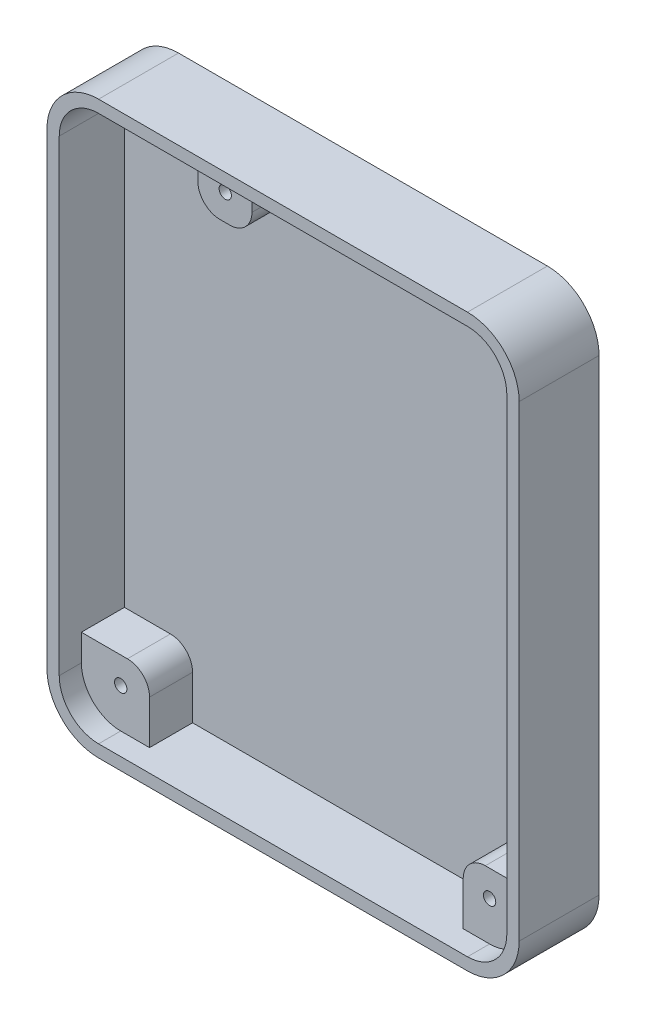
SolidWorks part; units mm, degrees
ref_plane "Спереди" through (0, 0, 0) normal (0, 0, 1) x (1, 0, 0)
ref_plane "Сверху" through (0, 0, 0) normal (0, 1, 0) x (1, 0, 0)
ref_plane "Справа" through (0, 0, 0) normal (1, 0, 0) x (0, 0, -1)
sketch "Эскиз1" plane through (0, 0, 0) normal (0, 0, 1) x (1, 0, 0)
  line L0 (36.05, 3) -> (35.95, 3)
  line L1 (35.95, 3) -> (35.95, 41)
  line L2 (35.95, 41) -> (36.05, 41)
  line L3 (36.05, 41) -> (36.05, 3)
  line L4 (3, 43.95) -> (3, 44.05)
  line L5 (3, 44.05) -> (33, 44.05)
  line L6 (33, 44.05) -> (33, 43.95)
  line L7 (33, 43.95) -> (3, 43.95)
  line L8 (0.05, 3) -> (-0.05, 3)
  line L9 (-0.05, 3) -> (-0.05, 41)
  line L10 (-0.05, 41) -> (0.05, 41)
  line L11 (0.05, 41) -> (0.05, 3)
  line L12 (3, -0.05) -> (3, 0.05)
  line L13 (3, 0.05) -> (33, 0.05)
  line L14 (33, 0.05) -> (33, -0.05)
  line L15 (33, -0.05) -> (3, -0.05)
  circle A0 centre (36, 3) radius 0.05
  circle A1 centre (36, 41) radius 0.05
  circle A2 centre (3, 44) radius 0.05
  circle A3 centre (33, 44) radius 0.05
  circle A4 centre (0, 3) radius 0.05
  circle A5 centre (0, 41) radius 0.05
  circle A6 centre (3, 0) radius 0.05
  circle A7 centre (33, 0) radius 0.05
  arc A8 (36, 41) -> (33, 44) centre (33, 41) ccw
  circle A9 centre (33, 44) radius 0.05
  circle A10 centre (36, 41) radius 0.05
  arc A11 (33, 0) -> (36, 3) centre (33, 3) ccw
  circle A12 centre (36, 3) radius 0.05
  circle A13 centre (33, 0) radius 0.05
  arc A14 (3, 44) -> (0, 41) centre (3, 41) ccw
  circle A15 centre (0, 41) radius 0.05
  circle A16 centre (3, 44) radius 0.05
  arc A17 (0, 3) -> (3, 0) centre (3, 3) ccw
  circle A18 centre (3, 0) radius 0.05
  circle A19 centre (0, 3) radius 0.05
  circle A20 centre (11.5, 42) radius 1
  circle A21 centre (33, 3) radius 1
  circle A22 centre (3, 3) radius 1
sketch "Эскиз2" plane through (0, 0, 0) normal (0, 0, 1) x (1, 0, 0)
  line L0 (3, 44.2) -> (33, 44.2)
  line L1 (36.2, 41) -> (36.2, 3)
  line L2 (-0.2, 41) -> (-0.2, 3)
  line L3 (3, -0.2) -> (33, -0.2)
  line L4 (3, 45.2) -> (33, 45.2)
  line L5 (37.2, 41) -> (37.2, 3)
  line L6 (3, -1.2) -> (33, -1.2)
  line L7 (-1.2, 41) -> (-1.2, 3)
  arc A2 (3, 44.2) -> (-0.2, 41) centre (3, 41) ccw
  arc A3 (3, 44.2) -> (-0.2, 41) centre (3, 41) ccw
  arc A5 (36.2, 41) -> (33, 44.2) centre (33, 41) ccw
  arc A6 (36.2, 41) -> (33, 44.2) centre (33, 41) ccw
  arc A8 (-0.2, 3) -> (3, -0.2) centre (3, 3) ccw
  arc A9 (-0.2, 3) -> (3, -0.2) centre (3, 3) ccw
  arc A10 (37.2, 41) -> (33, 45.2) centre (33, 41) ccw
  arc A11 (33, -0.2) -> (36.2, 3) centre (33, 3) ccw
  arc A12 (33, -0.2) -> (36.2, 3) centre (33, 3) ccw
  arc A13 (33, -1.2) -> (37.2, 3) centre (33, 3) ccw
  arc A14 (-1.2, 3) -> (3, -1.2) centre (3, 3) ccw
  arc A15 (3, 45.2) -> (-1.2, 41) centre (3, 41) ccw
  dimension "D5" = 1
  dimension "D1" = 0.2
  dimension "D2" = 0.2
  dimension "D3" = 0.2
  dimension "D4" = 0.2
extrude "Бобышка-Вытянуть1" add sketch "Эскиз2" along normal blind 6.5
sketch "Эскиз3" plane through (0, 0, 0) normal (0, 0, 1) x (1, 0, 0)
  line L0 (-1.2, 41) -> (-1.2, 3) construction
  line L1 (3, -1.2) -> (33, -1.2) construction
  line L2 (37.2, 3) -> (37.2, 41) construction
  line L3 (33, 45.2) -> (3, 45.2) construction
  line L4 (-1.2, 41) -> (-1.2, 3)
  line L5 (3, -1.2) -> (33, -1.2)
  line L6 (37.2, 3) -> (37.2, 41)
  line L7 (33, 45.2) -> (3, 45.2)
  arc A0 (-1.2, 3) -> (3, -1.2) centre (3, 3) ccw construction
  arc A1 (33, -1.2) -> (37.2, 3) centre (33, 3) ccw construction
  arc A2 (37.2, 41) -> (33, 45.2) centre (33, 41) ccw construction
  arc A3 (3, 45.2) -> (-1.2, 41) centre (3, 41) ccw construction
  arc A4 (-1.2, 3) -> (3, -1.2) centre (3, 3) ccw
  arc A5 (33, -1.2) -> (37.2, 3) centre (33, 3) ccw
  arc A6 (37.2, 41) -> (33, 45.2) centre (33, 41) ccw
  arc A7 (3, 45.2) -> (-1.2, 41) centre (3, 41) ccw
extrude "Бобышка-Вытянуть2" add sketch "Эскиз3" along normal blind 1.2
sketch "Эскиз4" plane through (0, 0, 1.2) normal (0, 0, 1) x (1, 0, 0)
  line L0 (33, 44.2) -> (3, 44.2) construction
  line L1 (9.2712, 44.2) -> (13.6696, 44.2)
  line L2 (9.2712, 44.2) -> (9.2712, 41.6633)
  line L3 (11.0712, 39.8633) -> (11.8696, 39.8633)
  line L4 (13.6696, 44.2) -> (13.6696, 41.6633)
  line L5 (-0.2, 3) -> (-0.2, 5.1581)
  line L6 (-0.2, 41) -> (-0.2, 3) construction
  line L7 (-0.2, 5.1581) -> (3.5421, 5.1581)
  line L8 (5.3421, 3.3581) -> (5.3421, -0.2)
  line L9 (3, -0.2) -> (33, -0.2) construction
  line L10 (5.3421, -0.2) -> (3, -0.2)
  line L11 (33, -0.2) -> (30.8511, -0.2)
  line L12 (3, -0.2) -> (33, -0.2) construction
  line L13 (30.8511, -0.2) -> (30.8511, 3.3374)
  line L14 (32.6511, 5.1374) -> (36.2, 5.1374)
  line L15 (36.2, 3) -> (36.2, 41) construction
  line L16 (36.2, 5.1374) -> (36.2, 3)
  arc A0 (11.8696, 39.8633) -> (13.6696, 41.6633) centre (11.8696, 41.6633) ccw
  arc A1 (9.2712, 41.6633) -> (11.0712, 39.8633) centre (11.0712, 41.6633) ccw
  arc A2 (-0.2, 3) -> (3, -0.2) centre (3, 3) ccw construction
  arc A3 (-0.2, 3) -> (3, -0.2) centre (3, 3) ccw
  arc A4 (3.5421, 5.1581) -> (5.3421, 3.3581) centre (3.5421, 3.3581) cw
  arc A5 (33, -0.2) -> (36.2, 3) centre (33, 3) ccw construction
  arc A6 (33, -0.2) -> (36.2, 3) centre (33, 3) ccw
  arc A7 (30.8511, 3.3374) -> (32.6511, 5.1374) centre (32.6511, 3.3374) cw
  circle A8 centre (11.5, 42) radius 0.5
  circle A9 centre (3, 3) radius 0.5
  circle A10 centre (33, 3) radius 0.5
  dimension "D1" = 1
  dimension "D2" = 1.8
  dimension "D3" = 1.8
extrude "Бобышка-Вытянуть3" add sketch "Эскиз4" along normal blind 3.5
